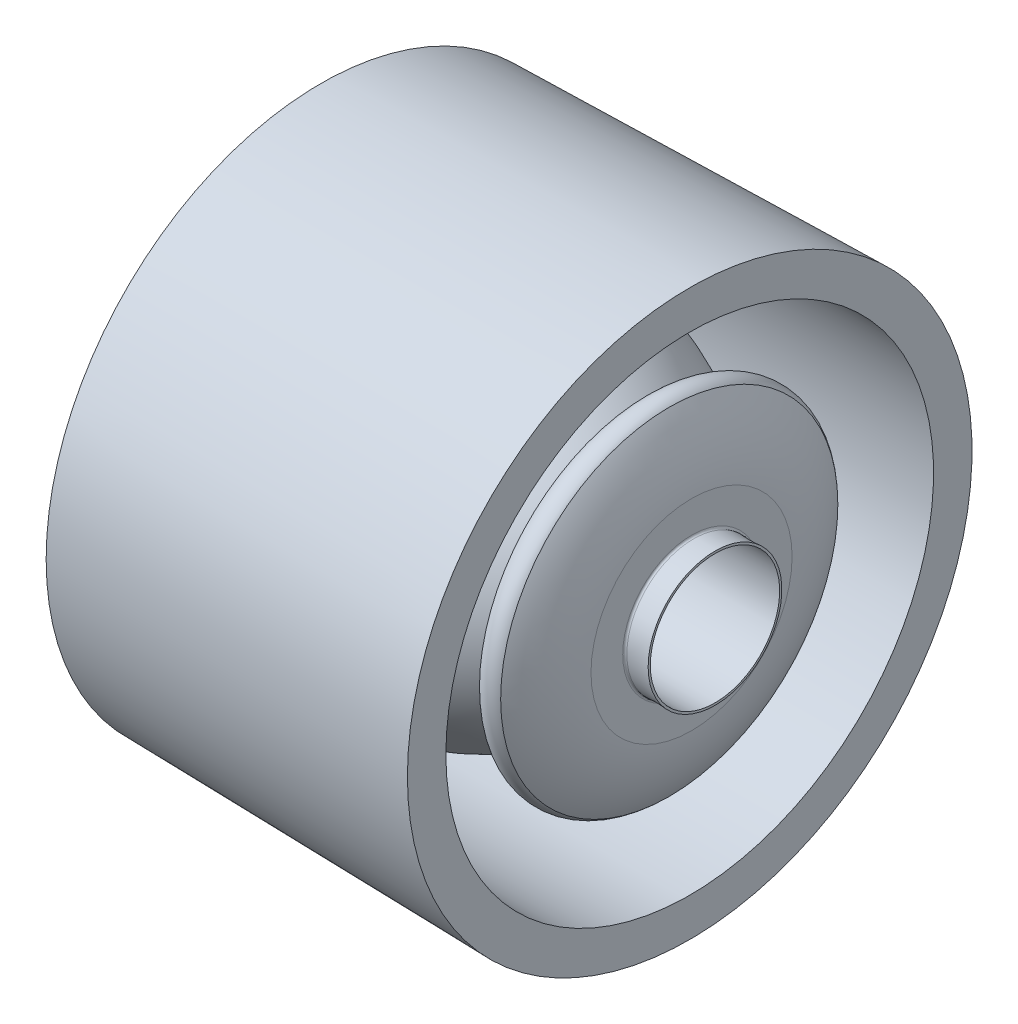
SolidWorks part; units mm, degrees
ref_plane "Front Plane" through (0, 0, 0) normal (0, 0, 1) x (1, 0, 0)
ref_plane "Top Plane" through (0, 0, 0) normal (0, 1, 0) x (1, 0, 0)
ref_plane "Right Plane" through (0, 0, 0) normal (1, 0, 0) x (0, 0, -1)
sketch "Sketch1" plane through (0, 0, 0) normal (0, 0, 1) x (1, 0, 0)
  line L0 (0, 0.889) -> (0, 6.477)
  line L1 (0, 0.889) -> (0, 6.477)
  line L2 (10.414, 33.1978) -> (10.719, 33.1978)
  line L3 (43.3699, 0) -> (43.3699, 4.5212)
  line L4 (43.3699, 0) -> (43.3699, 4.5212)
  line L5 (0, 0.889) -> (43.3699, 0)
  line L6 (43.3699, 4.5212) -> (11.3659, 4.5212)
  line L7 (34.7847, 25.5905) -> (34.7847, 25.3365)
  line L8 (0, 6.477) -> (10.414, 10.3886)
  line L9 (10.414, 10.3886) -> (10.414, 33.1978)
  line L11 (10.719, 10.6426) -> (10.719, 33.1978)
  line L12 (10.719, 10.6426) -> (11.371, 10.6426)
  line L14 (34.7847, 25.3365) -> (42.8572, 25.3365)
  line L15 (34.7847, 25.5905) -> (46.3417, 25.5905)
  line L16 (43.1778, 25.3365) -> (43.33, 25.3365)
  line L17 (43.1159, 33.1978) -> (43.1159, 25.6754) construction
  line L18 (43.0973, 25.2318) -> (43.1778, 25.3365)
  line L20 (43.3699, 33.1978) -> (43.3699, 25.5905) construction
  line L26 (10.719, 10.3886) -> (11.3659, 10.3886) construction
  line L27 (46.3417, 25.5905) -> (46.3417, 25.3365)
  line L28 (43.584, 25.1058) -> (43.584, 21.3741)
  line L29 (43.33, 25.3365) -> (43.33, 21.382)
  line L30 (43.584, 25.3365) -> (43.584, 21.3741) construction
  line L31 (38.6509, 13.5527) -> (38.4713, 13.3731)
  line L32 (11.3659, 10.3886) -> (11.3659, 4.5212)
  line L33 (43.33, 25.3365) -> (43.33, 21.3741) construction
  line L34 (10.719, 10.6426) -> (11.371, 10.6426) construction
  arc A0 (11.3659, 10.3886) -> (43.0973, 25.2318) centre (12.8815, 48.4873) ccw
  arc A1 (11.371, 10.6426) -> (42.8572, 25.3365) centre (12.8815, 48.4873) ccw
  arc A2 (43.8159, 25.3589) -> (46.3417, 25.3365) centre (44.9629, 12.2505) cw
  arc A3 (11.371, 10.6426) -> (43.1159, 25.6754) centre (12.8815, 48.4873) ccw construction
  arc A4 (43.584, 25.1058) -> (43.8159, 25.3589) centre (43.838, 25.1058) cw
  arc A5 (43.584, 21.3741) -> (40.9631, 13.3731) centre (26.9169, 22.4042) cw
  arc A6 (43.33, 21.382) -> (40.7647, 13.5342) centre (26.9169, 22.4042) cw
  arc A7 (38.4713, 13.3731) -> (40.9631, 13.3731) centre (39.7172, 14.619) ccw
  arc A8 (11.3659, 10.3886) -> (43.3699, 25.5905) centre (12.8815, 48.4873) ccw construction
  arc A9 (38.6509, 13.5527) -> (40.7647, 13.5342) centre (39.7172, 14.619) ccw
  arc A11 (43.3305, 21.3898) -> (40.7494, 13.5105) centre (26.9169, 22.4042) cw construction
  arc A12 (38.6509, 13.5527) -> (40.7834, 13.5527) centre (39.7172, 14.619) ccw construction
  point P20 (43.3699, 25.3365)
  point P21 (2.5008, 27.4949)
  point P22 (43.1162, 25.6023)
  point P26 (57.9519, 23.4434)
  point P44 (43.584, 25.3365)
  dimension "D14" = 0.254
  dimension "D2" = 10.414
  dimension "D3" = 11.557
  dimension "D4" = 32.3088
  dimension "D5" = 5.588
  dimension "D6" = 32.004
  dimension "D7" = 4.5212
  dimension "D8" = 9.4996
  dimension "D10" = 0.254
  dimension "D11" = 3.9624
  dimension "D12" = 0.254
sketch "Sketch3" plane through (0, 0, 0) normal (1, 0, 0) x (0, 0, -1)
revolve "Revolve14" add sketch "Sketch1" angle 360 about L2
